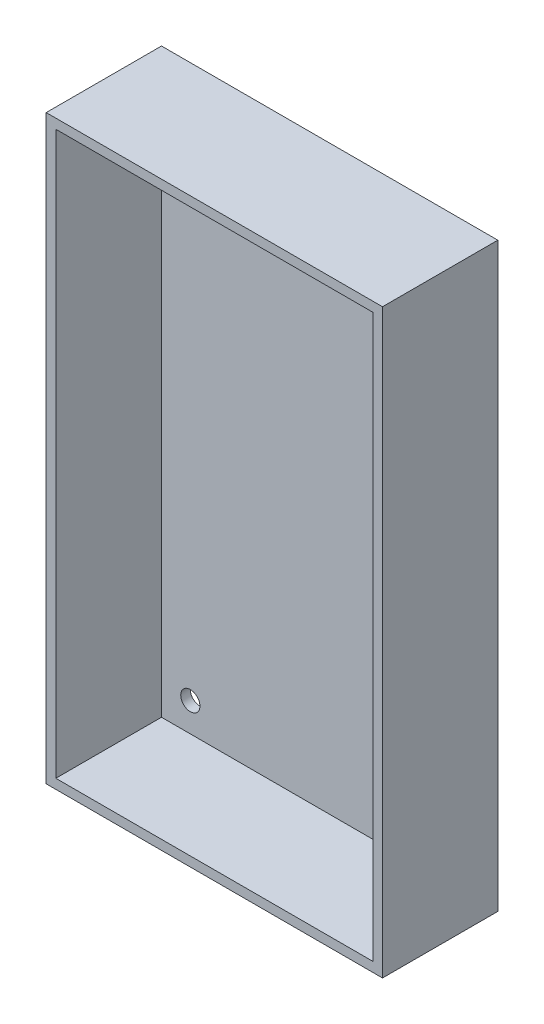
SolidWorks part; units mm, degrees
ref_plane "Alzado" through (0, 0, 0) normal (0, 0, 1) x (1, 0, 0)
ref_plane "Planta" through (0, 0, 0) normal (0, 1, 0) x (1, 0, 0)
ref_plane "Vista lateral" through (0, 0, 0) normal (1, 0, 0) x (0, 0, -1)
sketch "Croquis1" plane through (0, 0, 0) normal (0, 0, 1) x (1, 0, 0)
  line L1 (-35, 60.5) -> (35, 60.5)
  line L2 (-35, 60.5) -> (-35, -60.5)
  line L3 (-35, -60.5) -> (35, -60.5)
  line L4 (35, 60.5) -> (35, -60.5)
  line L5 (-35, 60.5) -> (35, -60.5) construction
  line L6 (-35, -60.5) -> (35, 60.5) construction
  point P0 (0, 0)
  dimension "D1" = 70
  dimension "D2" = 121
extrude "Saliente-Extruir1" add sketch "Croquis1" along normal blind 2 contours L2 L3 L4 L1
sketch "Croquis2" plane through (0, 0, 2) normal (0, 0, 1) x (1, 0, 0)
  line L0 (-35, 60.5) -> (35, 60.5) construction
  line L1 (-33, 58.5) -> (33, 58.5)
  line L2 (-33, 58.5) -> (-33, -58.5)
  line L3 (-33, -58.5) -> (33, -58.5)
  line L4 (33, 58.5) -> (33, -58.5)
  line L5 (-33, 58.5) -> (33, -58.5) construction
  line L6 (-33, -58.5) -> (33, 58.5) construction
  line L7 (-35, 60.5) -> (-35, -60.5) construction
  line L8 (-35, 60.5) -> (-35, -60.5)
  line L9 (-35, 60.5) -> (35, 60.5)
  line L10 (35, 60.5) -> (35, -60.5) construction
  line L11 (35, 60.5) -> (35, -60.5)
  point P0 (0, 0)
  line M5 (35, 60.5) -> (-35, 60.5)
  line M6 (-35, 60.5) -> (-35, -60.5)
  line M7 (-35, -60.5) -> (35, -60.5)
  line M8 (35, -60.5) -> (35, 60.5)
  dimension "D1" = 2
  dimension "D2" = 2
extrude "Saliente-Extruir2" add sketch "Croquis2" along normal blind 22 contours L1 L4 L3 L2 M8 M5 M6 M7
sketch "Croquis3" plane through (0, 0, 0) normal (0, 0, -1) x (-1, 0, 0)
  line L0 (0, 63.9377) -> (0, -63.9377) construction
  line L1 (-80.0648, 0) -> (80.0648, 0) construction
  line L2 (-35, 60.5) -> (-35, -60.5) construction
  line L3 (35, 60.5) -> (-35, 60.5) construction
  circle A0 centre (-27, 52.5) radius 2
  circle A1 centre (-27, -52.5) radius 2
  circle A2 centre (27, -52.5) radius 2
  circle A3 centre (27, 52.5) radius 2
  point P0 (-27, 52.5)
  point P4 (0, 0)
  point P8 (0, 0)
  dimension "D3" = 4
  dimension "D1" = 8
  dimension "D2" = 8
extrude "Cortar-Extruir1" cut sketch "Croquis3" against normal blind 10
